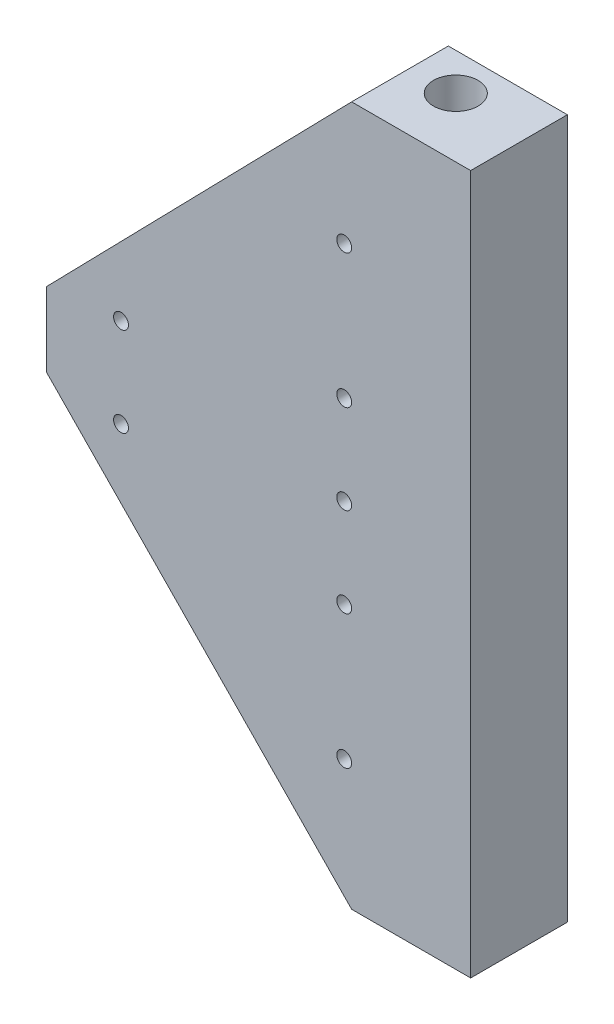
SolidWorks part; units mm, degrees
material "1060-H14"
ref_plane "Front Plane" through (0, 0, 0) normal (0, 0, 1) x (1, 0, 0)
ref_plane "Top Plane" through (0, 0, 0) normal (0, 1, 0) x (1, 0, 0)
ref_plane "Right Plane" through (0, 0, 0) normal (1, 0, 0) x (0, 0, -1)
sketch "Sketch2" plane through (0, 0, 0) normal (0, 0, -1) x (1, 0, 0)
  line L0 (-35, 0) -> (270, 0) construction
  line L2 (115, -125.4) -> (115, -100.4)
  line L3 (195, 125.4) -> (115, 125.4)
  line L4 (195, 125.4) -> (195, 100.4)
  line L5 (195, 100.4) -> (115, 100.4)
  line L6 (115, 125.4) -> (115, 100.4)
  line L7 (195, -100.4) -> (115, -100.4)
  line L8 (195, -125.4) -> (195, -100.4)
  line L9 (195, -125.4) -> (115, -125.4)
  line L10 (-35, 20) -> (-35, 0) construction
  line L11 (-70, 20) -> (0, 20)
  line L12 (-70, 20) -> (-70, 10)
  line L13 (-70, 10) -> (0, 10)
  line L14 (0, 20) -> (0, 10)
  line L15 (0, -20) -> (0, -10)
  line L16 (-70, -10) -> (0, -10)
  line L17 (-70, -20) -> (-70, -10)
  line L18 (-70, -20) -> (0, -20)
  line L20 (115, 235) -> (195, 235)
  line L21 (115, 235) -> (115, 205)
  line L22 (115, 205) -> (195, 205)
  line L23 (195, 235) -> (195, 205)
  line L24 (115, -235) -> (115, -205)
  line L25 (115, -235) -> (195, -235)
  line L26 (195, -235) -> (195, -205)
  line L27 (115, -205) -> (195, -205)
  dimension "D1" = 80
  dimension "D2" = 25
  dimension "D3" = 100.4
  dimension "D4" = 150
  dimension "D5" = 10
  dimension "D6" = 70
  dimension "D7" = 10
  dimension "D9" = 30
extrude "Boss-Extrude1" add sketch "Sketch2" along normal blind 65
sketch "Sketch3" plane through (0, 0, 0) normal (0, -1, 0) x (1, 0, 0)
  line L0 (145, -80) -> (145, 0) construction
  line L1 (-70, -65) -> (-70, 0) construction
  line L3 (195, -40) -> (115, -40) construction
  line L5 (0, 0) -> (-43.6216, -37.1774)
  line L6 (-54, -25) -> (-54, 15) construction
  line L7 (0, 0) -> (5, 0)
  line L8 (5, 0) -> (5, -70)
  line L9 (5, -70) -> (-75, -70)
  line L10 (-75, -70) -> (-75, -25)
  line L11 (-75, -25) -> (-70, -25)
  line L12 (0, -65) -> (0, 0) construction
  line L14 (0, -65) -> (-70, -65) construction
  circle A0 centre (145, -40) radius 15
  circle A1 centre (-54, -25) radius 6.25
  arc A2 (-70, -25) -> (-43.6216, -37.1774) centre (-54, -25) ccw
  dimension "D1" = 30
  dimension "D2" = 12.5
  dimension "D4" = 16
  dimension "D3" = 16
  dimension "D5" = 25
  dimension "D6" = 5
  dimension "D7" = 5
  dimension "D8" = 5
extrude "Cut-Extrude1" cut sketch "Sketch3" against normal through all and the other way through all contours A1
sketch "Sketch6" plane through (0, 0, 0) normal (0, 0, 1) x (1, 0, 0)
  line L0 (195, 235) -> (195, -235)
  line L1 (195, -235) -> (115, -235)
  line L2 (115, -235) -> (-90, -25)
  line L3 (-90, -25) -> (-90, 25)
  line L4 (-90, 25) -> (115, 235)
  line L5 (115, 235) -> (195, 235)
  line L6 (0, 0) -> (-90, 0) construction
  dimension "D1" = 25
  dimension "D2" = 25
  dimension "D3" = 90
extrude "Boss-Extrude5" add sketch "Sketch6" against normal blind 10
sketch "Sketch7" plane through (0, 0, 0) normal (0, 0, 1) x (1, 0, 0)
  line L0 (110, 150) -> (110, -150) construction
  line L2 (70, 0) -> (286.169, 0) construction
  line L3 (-40, 150) -> (-40, -150) construction
  line L4 (110, 150) -> (-40, 150) construction
  line L5 (110, 0) -> (70, 0) construction
  line L6 (-40, 0) -> (70, 0) construction
  circle A3 centre (110, 150) radius 5
  circle A4 centre (110, 60) radius 5
  circle A5 centre (110, 0) radius 5
  circle A7 centre (-40, 30) radius 5
  circle A8 centre (-40, -30) radius 5
  circle A9 centre (110, -60) radius 5
  circle A10 centre (110, -150) radius 5
  dimension "D3" = 10
  dimension "D5" = 60
  dimension "D1" = 40
  dimension "D2" = 110
  dimension "D4" = 40
  dimension "D6" = 120
  dimension "D7" = 90
extrude "Cut-Extrude2" cut sketch "Sketch7" against normal up to next
sketch "Sketch8" plane through (195, 0, 0) normal (1, 0, 0) x (0, 0, -1)
  line L1 (0, 235) -> (65, 235)
  line L2 (0, 235) -> (0, -235)
  line L3 (0, -235) -> (65, -235)
  line L4 (65, 235) -> (65, -235)
extrude "Boss-Extrude6" add sketch "Sketch8" against normal blind 3
